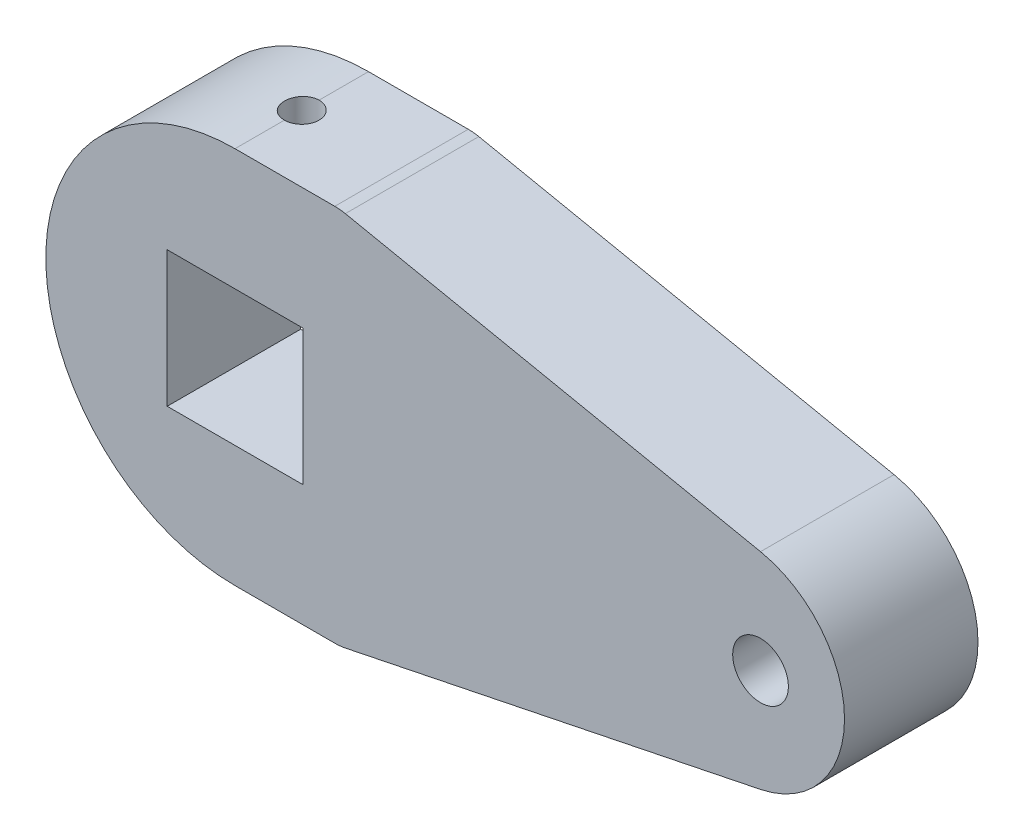
SolidWorks part; units mm, degrees
material "ABS"
ref_plane "Front Plane" through (0, 0, 0) normal (0, 0, 1) x (1, 0, 0)
ref_plane "Top Plane" through (0, 0, 0) normal (0, 1, 0) x (1, 0, 0)
ref_plane "Right Plane" through (0, 0, 0) normal (1, 0, 0) x (0, 0, -1)
sketch "Sketch1" plane through (0, 0, 0) normal (0, 0, 1) x (1, 0, 0)
  line L0 (50, 9.7961) -> (10, 18)
  line L1 (-6.45, 6.45) -> (6.45, 6.45)
  line L2 (-6.45, 6.45) -> (-6.45, -6.45)
  line L3 (-6.45, -6.45) -> (6.45, -6.45)
  line L4 (6.45, 6.45) -> (6.45, -6.45)
  line L5 (10, -18) -> (50, -9.7961)
  line L6 (10, 18) -> (0, 18)
  line L7 (10, -18) -> (0, -18)
  circle A0 centre (50, 0) radius 2.5 construction
  arc A1 (50, 9.7961) -> (50, -9.7961) centre (47.9908, 0) cw
  arc A3 (0, 18) -> (0, -18) centre (0, 0) ccw
  point P6 (6.45, 0)
  point P8 (0, 6.45)
  dimension "D2" = 5
  dimension "D4" = 10
  dimension "D5" = 10
  dimension "D6" = 18
  dimension "D1" = 12.9
  dimension "D3" = 50
extrude "Boss-Extrude1" add sketch "Sketch1" along normal blind 12.7 contours L0 L5 A1
sketch "Sketch2" plane through (0, 18, 0) normal (0, 1, 0) x (1, 0, 0)
  line L0 (0, -12.7) -> (0, 0) construction
  circle A0 centre (0, -6.35) radius 2 construction
  dimension "D1" = 4
hole_wizard "Tap Drill for M4x0.7 Tap1" positions "3DSketch1" profile "Sketch3" hole size "M4x0.7" standard "ANSI Metric"
sketch3d "3DSketch1"
  point P0 (0, 18, 6.35)
sketch "Sketch3" plane through (0, 18, 6.35) normal (1, 0, 0) x (0, 0, 1)
  line L0 (0, 0) -> (0, 11.55)
  line L1 (0, 11.55) -> (1.65, 11.55)
  line L2 (1.65, 11.55) -> (1.65, 0)
  line L5 (1.65, 0) -> (0, 0)
  line L11 (0, -6.35) -> (0, 107.95) construction
  dimension "Thru Hole Dia." = 3.3
  dimension "Thru Hole Depth" = 11.55
hole_wizard "M5 Clearance Hole1" positions "3DSketch2" profile "Sketch4" hole size "M5" standard "ANSI Metric" end condition up to next
sketch3d "3DSketch2"
  point P0 (50, 0, 0)
sketch "Sketch4" plane through (50, 0, 0) normal (1, 0, 0) x (0, 1, 0)
  line L0 (0, 0) -> (0, 12.7)
  line L1 (0, 12.7) -> (2.65, 12.7)
  line L2 (2.65, 12.7) -> (2.65, 0)
  line L5 (2.65, 0) -> (0, 0)
  line L11 (0, -6.35) -> (0, 107.95) construction
  dimension "Thru Hole Dia." = 5.3
  dimension "Thru Hole Depth" = 12.7
fillet "Fillet1" radius 5 2 edges at (10, -18, 6.35) (10, 18, 6.35)
